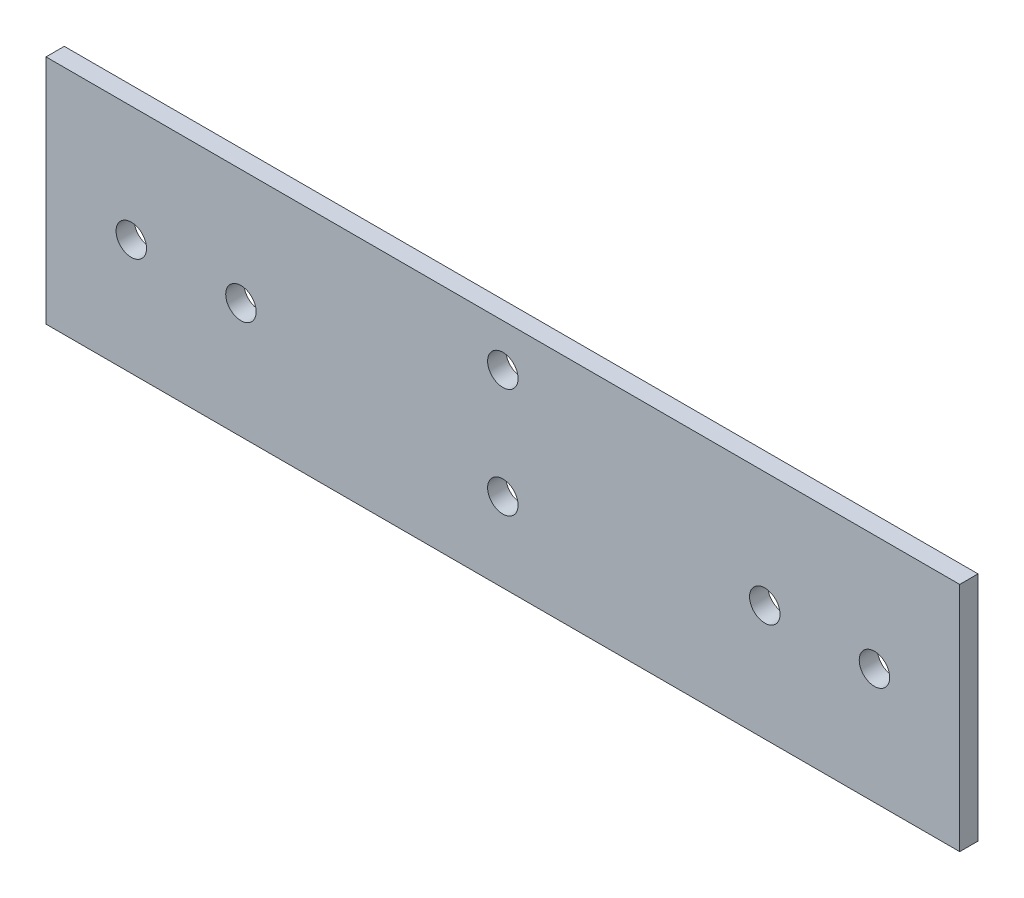
SolidWorks part; units mm, degrees
ref_plane "前基準面" through (0, 0, 0) normal (0, 0, 1) x (1, 0, 0)
ref_plane "上基準面" through (0, 0, 0) normal (0, 1, 0) x (1, 0, 0)
ref_plane "右基準面" through (0, 0, 0) normal (1, 0, 0) x (0, 0, -1)
sketch "草圖1" plane through (0, 0, 0) normal (0, 0, 1) x (1, 0, 0)
  line L1 (-75, 19) -> (75, 19)
  line L2 (-75, 19) -> (-75, -19)
  line L3 (-75, -19) -> (75, -19)
  line L4 (75, 19) -> (75, -19)
  line L5 (-75, 19) -> (75, -19) construction
  line L6 (-75, -19) -> (75, 19) construction
  point P0 (0, 0)
  dimension "D1" = 38
  dimension "D2" = 150
extrude "填料-伸長1" add sketch "草圖1" along normal blind 3
sketch "草圖2" plane through (0, 0, 0) normal (0, 0, -1) x (-1, 0, 0)
  line L5 (-75, -19) -> (-75, 19) construction
  circle A0 centre (-61, 0) radius 2.5
  circle A1 centre (-43, 0) radius 2.5
  dimension "D3" = 5
  dimension "D1" = 14
  dimension "D5" = 18
extrude "除料-伸長1" cut sketch "草圖2" against normal up to next
mirror "鏡射1" about plane through (0, 0, 0) normal (1, 0, 0) of "除料-伸長1"
sketch "草圖4" plane through (0, 0, 0) normal (0, 0, -1) x (-1, 0, 0)
  line L6 (-75, 19) -> (75, 19) construction
  circle A0 centre (0, -6) radius 2.5
  circle A1 centre (0, 12) radius 2.5
  dimension "D3" = 18
  dimension "D5" = 5
  dimension "D1" = 7
extrude "除料-伸長2" cut sketch "草圖4" against normal up to next
